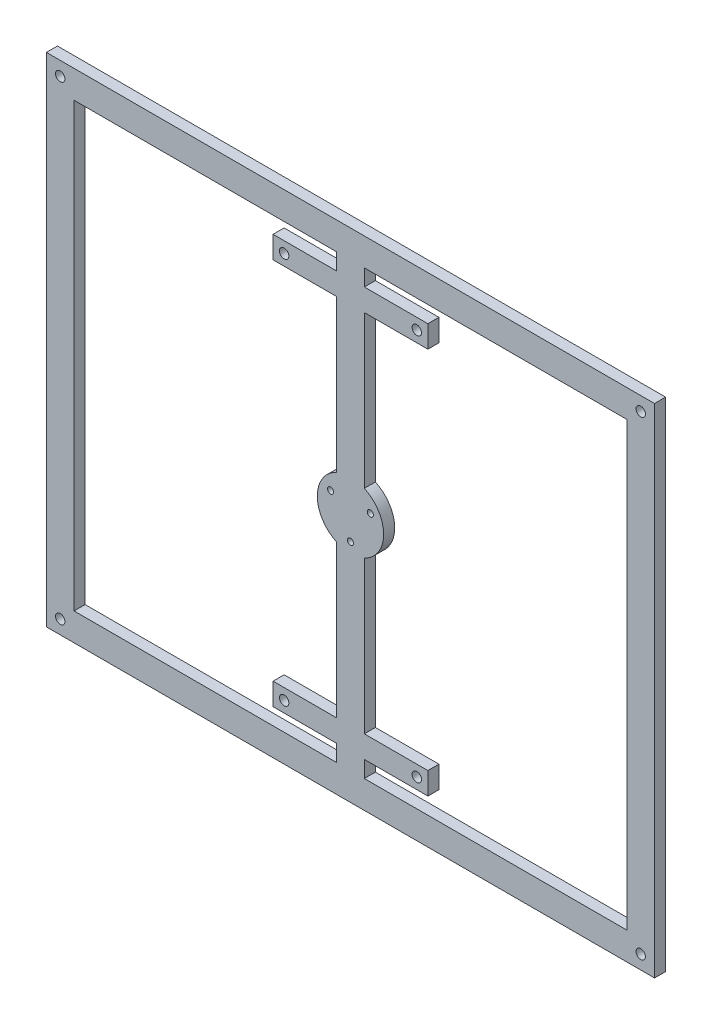
SolidWorks part; units mm, degrees
material "6061-T6 (SS)"
ref_plane "Front Plane" through (0, 0, 0) normal (0, 0, 1) x (1, 0, 0)
ref_plane "Top Plane" through (0, 0, 0) normal (0, 1, 0) x (1, 0, 0)
ref_plane "Right Plane" through (0, 0, 0) normal (1, 0, 0) x (0, 0, -1)
sketch "Sketch1" plane through (0, 0, 0) normal (0, 0, 1) x (1, 0, 0)
  line L1 (-110, -90) -> (110, -90)
  line L2 (-110, -90) -> (-110, 90)
  line L3 (-110, 90) -> (110, 90)
  line L4 (110, -90) -> (110, 90)
  line L6 (-100, -80) -> (100, -80)
  line L7 (-100, -80) -> (-100, 80)
  line L8 (-100, 80) -> (100, 80)
  line L9 (100, -80) -> (100, 80)
extrude "Lower_Perimeter" add sketch "Sketch1" along normal blind 4 from offset 8
sketch "Sketch2" plane through (0, 0, 0) normal (0, 0, 1) x (1, 0, 0)
  line L1 (-5, -85) -> (5, -85)
  line L2 (-5, -85) -> (-5, 85)
  line L3 (-5, 85) -> (5, 85)
  line L4 (5, -85) -> (5, 85)
extrude "Centre_Spine" add sketch "Sketch2" along normal blind 4 from offset 8
sketch "Sketch3" plane through (0, 0, 0) normal (0, 0, 1) x (1, 0, 0)
  circle A0 centre (0, 0) radius 12
extrude "Pedestal_Landing" add sketch "Sketch3" along normal blind 4 from offset 8
sketch "Sketch4" plane through (0, 0, 0) normal (0, 0, 1) x (1, 0, 0)
  line L1 (-28, -74) -> (28, -74)
  line L2 (-28, -74) -> (-28, -66)
  line L3 (-28, -66) -> (28, -66)
  line L4 (28, -74) -> (28, -66)
extrude "Base_Landing_-70" add sketch "Sketch4" along normal blind 4 from offset 8
sketch "Sketch5" plane through (0, 0, 0) normal (0, 0, 1) x (1, 0, 0)
  line L1 (-28, 66) -> (28, 66)
  line L2 (-28, 66) -> (-28, 74)
  line L3 (-28, 74) -> (28, 74)
  line L4 (28, 66) -> (28, 74)
extrude "Base_Landing_70" add sketch "Sketch5" along normal blind 4 from offset 8
sketch "Sketch6" plane through (0, 0, -4) normal (0, 0, 1) x (1, 0, 0)
  circle A0 centre (-105, -85) radius 1.7
  circle A1 centre (-105, 85) radius 1.7
  circle A2 centre (105, -85) radius 1.7
  circle A3 centre (105, 85) radius 1.7
  circle A4 centre (-24, -70) radius 1.7
  circle A5 centre (-24, 70) radius 1.7
  circle A6 centre (24, -70) radius 1.7
  circle A7 centre (24, 70) radius 1.7
extrude "Eight_M3_Clearance" cut sketch "Sketch6" against normal blind 4.01
sketch "Sketch7" plane through (0, 0, -4) normal (0, 0, 1) x (1, 0, 0)
  circle A0 centre (7.188, 4.15) radius 1.1
  circle A1 centre (-7.188, 4.15) radius 1.1
  circle A2 centre (0, -8.3) radius 1.1
extrude "Pedestal_Three_M2_Clearance" cut sketch "Sketch7" against normal blind 4.01
